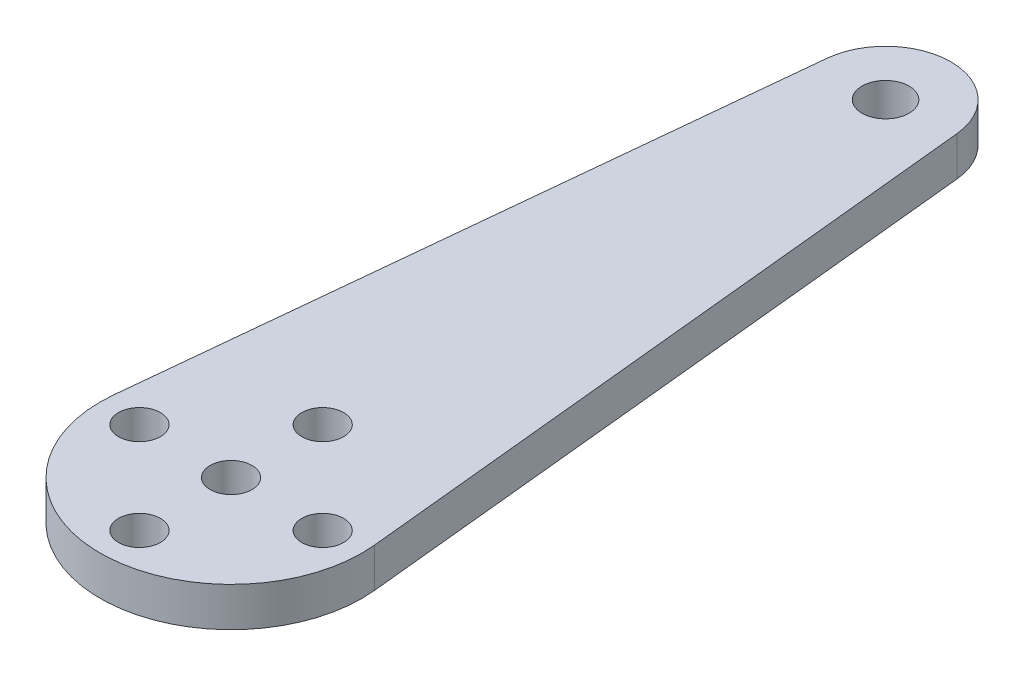
SolidWorks part; units mm, degrees
ref_plane "Front" through (0, 0, 0) normal (0, 0, 1) x (1, 0, 0)
ref_plane "Top" through (0, 0, 0) normal (0, 1, 0) x (1, 0, 0)
ref_plane "Right" through (0, 0, 0) normal (1, 0, 0) x (0, 0, -1)
sketch "草图1" plane through (0, 0, 0) normal (0, 1, 0) x (1, 0, 0)
  line L0 (-10.354, -10.354) -> (10.2454, 10.2454) construction
  line L1 (-12.4824, 12.4824) -> (12.4824, -12.4824) construction
  line L2 (0, -12.0909) -> (0, 12.0909) construction
  line L3 (-5.0249, 50.0025) -> (-5005.0249, -49699.3694) construction
  line L4 (5.1315, 48.942) -> (5005.1315, -49700.4298) construction
  line L5 (-4.9749, 50.5) -> (-9.9499, 1)
  line L6 (9.9499, 1) -> (4.9749, 50.5)
  circle A0 centre (0, 0) radius 10
  circle A1 centre (0, 0) radius 1.6
  circle A2 centre (0, 7) radius 1.6
  circle A3 centre (7, 0) radius 1.6
  circle A4 centre (0, -7) radius 1.6
  circle A5 centre (-7, 0) radius 1.6
  circle A6 centre (0, 50) radius 1.8
  circle A7 centre (0, 50) radius 5
  point P9 (0, 0)
  point P12 (0, 0)
  point P15 (0, 0)
  point P27 (-4.9749, 50.5)
  point P28 (4.9749, 50.5)
  point P30 (-9.9499, 1)
  point P31 (9.9499, 1)
  dimension "D1" = 20
  dimension "D2" = 3.2
  dimension "D3" = 3.2
  dimension "D7" = 50
  dimension "D8" = 3.6
  dimension "D9" = 10
  dimension "D4" = 7
  dimension "D5" = 90
  dimension "D6" = 45
extrude "凸台-拉伸1" add sketch "草图1" along normal blind 3 contours A7 A6 | A7 L5 A0 L6 | A0 A3 A2 A1 A4 A5
